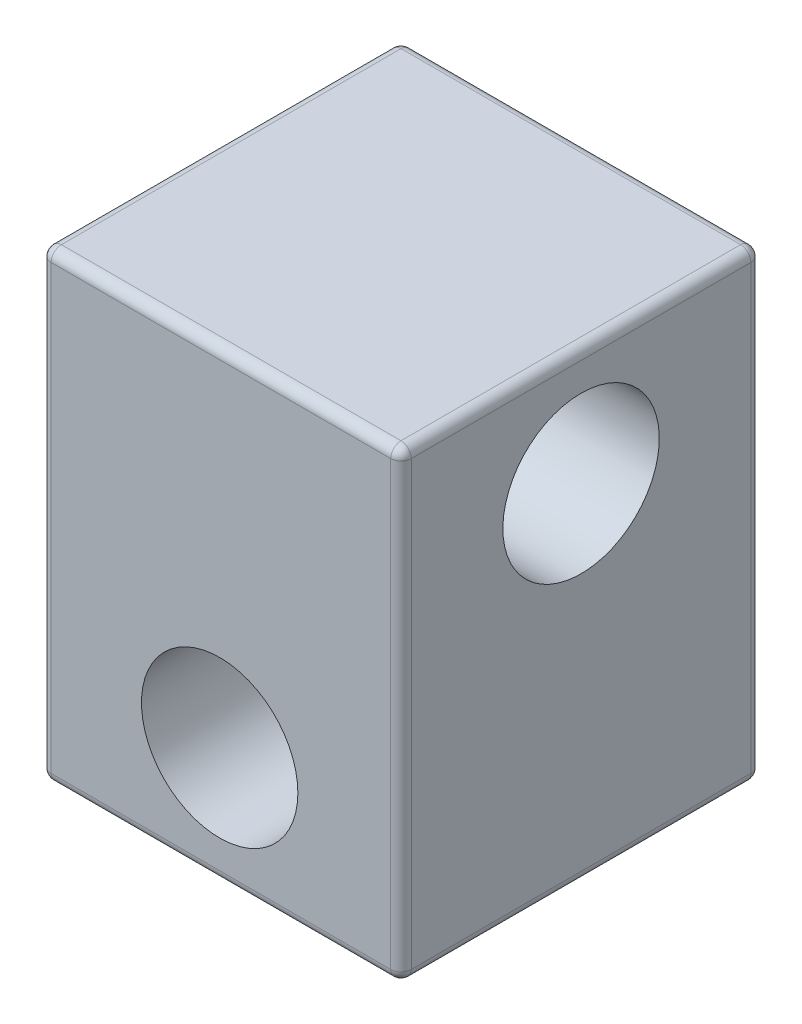
SolidWorks part; units mm, degrees
ref_plane "Piano frontale" through (0, 0, 0) normal (0, 0, 1) x (1, 0, 0)
ref_plane "Piano superiore" through (0, 0, 0) normal (0, 1, 0) x (1, 0, 0)
ref_plane "Piano destro" through (0, 0, 0) normal (1, 0, 0) x (0, 0, -1)
sketch "Schizzo1" plane through (0, 0, 0) normal (0, 0, 1) x (1, 0, 0)
  line L1 (-17.378, 22.5) -> (17.622, 22.5)
  line L2 (-17.378, 22.5) -> (-17.378, -22.5)
  line L3 (-17.378, -22.5) -> (17.622, -22.5)
  line L4 (17.622, 22.5) -> (17.622, -22.5)
  circle A0 centre (0, -11.15) radius 7.6
  point P6 (0, -18.75)
  point P7 (0, -3.55)
  dimension "D3" = 15.2
  dimension "D4" = 3.75
  dimension "D1" = 35
  dimension "D2" = 45
extrude "Estrusione-Estrusione1" add sketch "Schizzo1" along normal blind 35
sketch "Schizzo3" plane through (17.622, 0, 0) normal (1, 0, 0) x (0, 0, -1)
  line L1 (-35, 22.5) -> (0, 22.5) construction
  circle A0 centre (-17.5, 11.15) radius 7.6
  point P4 (-17.5, 18.75)
  point P6 (-17.5, 22.5)
  dimension "D1" = 15.2
  dimension "D2" = 3.75
extrude "Taglio-Estrusione1" cut sketch "Schizzo3" against normal blind 35
fillet "Raccordo1" radius 1 12 edges at (0.122, -22.5, 0) (17.622, -22.5, 17.5) (17.622, 0, 0) (17.622, 0, 35) (0.122, -22.5, 35) (-17.378, -22.5, 17.5) (-17.378, 0, 0) (-17.378, 0, 35) (0.122, 22.5, 0) (17.622, 22.5, 17.5) (0.122, 22.5, 35) (-17.378, 22.5, 17.5)
